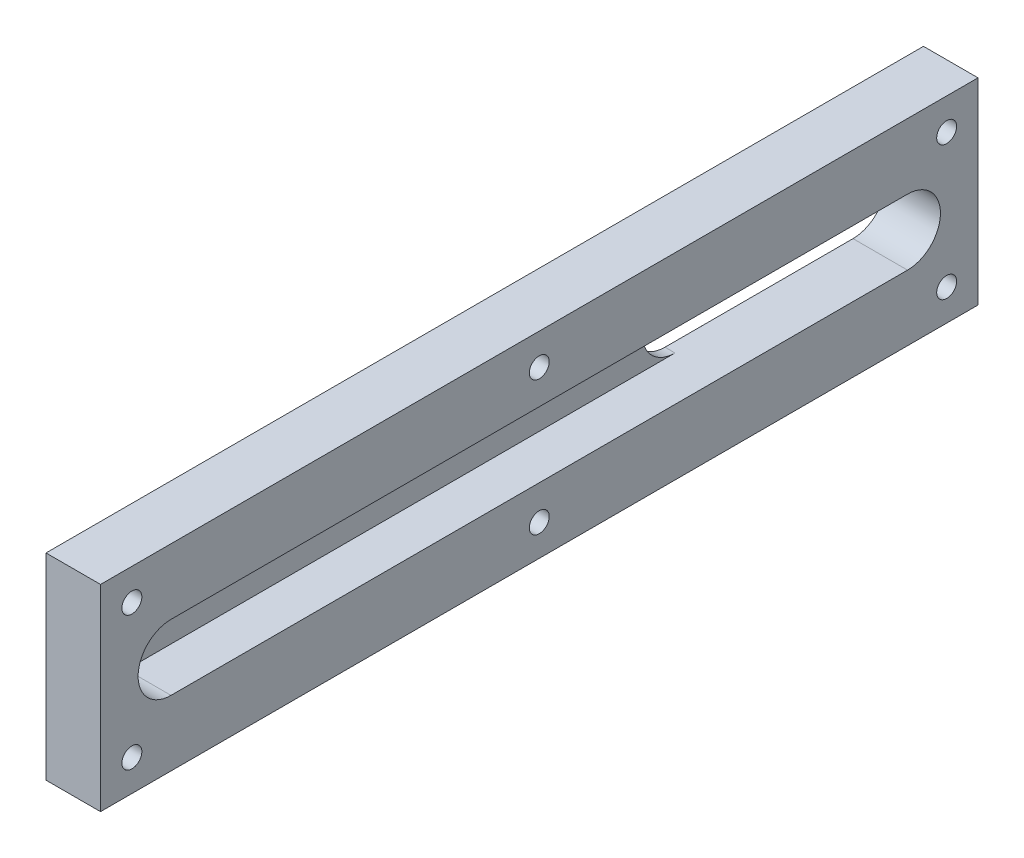
SolidWorks part; units mm, degrees
material "Delrin 2700 NC010, Low Viscosity Acetal Copolymer (SS)"
ref_plane "Front" through (0, 0, 0) normal (0, 0, 1) x (1, 0, 0)
ref_plane "Top" through (0, 0, 0) normal (0, 1, 0) x (1, 0, 0)
ref_plane "Right" through (0, 0, 0) normal (1, 0, 0) x (0, 0, -1)
sketch "Sketch1" plane through (0, 0, 0) normal (1, 0, 0) x (0, 0, -1)
  line L0 (-74.6213, 0) -> (74.6213, 0) construction
  line L1 (88.9, -19.939) -> (-88.9, -19.939)
  line L2 (88.9, -19.939) -> (88.9, 19.939)
  line L3 (88.9, 19.939) -> (-88.9, 19.939)
  line L4 (-88.9, -19.939) -> (-88.9, 19.939)
  line L5 (88.9, -19.939) -> (-88.9, 19.939) construction
  line L6 (88.9, 19.939) -> (-88.9, -19.939) construction
  line L7 (-74.6213, 6.6675) -> (74.6213, 6.6675)
  line L8 (-74.6213, -6.6675) -> (74.6213, -6.6675)
  arc A0 (-74.6213, 6.6675) -> (-74.6213, -6.6675) centre (-74.6213, 0) ccw
  arc A1 (74.6213, -6.6675) -> (74.6213, 6.6675) centre (74.6213, 0) ccw
  point P0 (0, 0)
  point P8 (0, 0)
  dimension "D4" = 13.335
  dimension "D1" = 149.2426
  dimension "D2" = 177.8
  dimension "D3" = 39.878
extrude "Boss-Extrude1" add sketch "Sketch1" along normal blind 11.049
hole_wizard "#10-32 Tapped Hole1" positions "Sketch3" profile "Sketch4" tap size "#10-32" standard "ANSI Inch" end condition through all
sketch "Sketch3" plane through (11.049, 0, 0) normal (1, 0, 0) x (0, 0, -1)
  line L0 (-82.55, 13.589) -> (0, 13.589) construction
  line L1 (0, 13.589) -> (82.55, 13.589) construction
  line L3 (-82.55, 19.939) -> (-82.55, 13.589) construction
  line L4 (88.9, 19.939) -> (-88.9, 19.939) construction
  line L5 (-82.55, 13.589) -> (-82.55, -13.589) construction
  line L6 (-82.55, -13.589) -> (-82.55, -19.939) construction
  line L7 (-88.9, -19.939) -> (88.9, -19.939) construction
  line L8 (-88.9, 19.939) -> (-88.9, -19.939) construction
  point P0 (-82.55, 13.589)
  point P2 (-82.55, -13.589)
  point P4 (0, -13.589)
  point P6 (82.55, -13.589)
  point P8 (82.55, 13.589)
  point P10 (0, 13.589)
  dimension "D1" = 6.35
  dimension "D2" = 6.35
sketch "Sketch4" plane through (11.049, 13.589, 82.55) normal (0, 1, 0) x (0, 0, -1)
  line L0 (0, 0) -> (0, 11.049)
  line L1 (0, 11.049) -> (2.0193, 11.049)
  line L2 (2.0193, 11.049) -> (2.0193, 0)
  line L5 (2.0193, 0) -> (0, 0)
  line L11 (0, -6.35) -> (0, 107.95) construction
  dimension "Thru Tap Drill Dia." = 4.0386
  dimension "Thru Tap Drill Depth" = 11.049
cosmetic thread "Hole Thread1" parameters "D2"=4.826
cosmetic thread "Hole Thread2" parameters "D2"=4.826
cosmetic thread "Hole Thread3" parameters "D2"=4.826
cosmetic thread "Hole Thread4" parameters "D2"=4.826
cosmetic thread "Hole Thread5" parameters "D2"=4.826
cosmetic thread "Hole Thread6" parameters "D2"=4.826
sketch "Sketch5" plane through (0, 0, 0) normal (-1, 0, 0) x (0, 0, 1)
  line L6 (-74.6213, -6.6675) -> (74.6213, -6.6675)
  line L7 (74.6213, 6.6675) -> (-74.6213, 6.6675)
  line L8 (-36.5213, -6.6675) -> (74.6213, -6.6675)
  line L9 (74.6213, 6.6675) -> (-36.5213, 6.6675)
  arc A2 (-36.5213, 6.6675) -> (-36.5213, -6.6675) centre (-36.5213, 0) cw
  arc A6 (-74.6213, 6.6675) -> (-74.6213, -6.6675) centre (-74.6213, 0) ccw construction
  arc A7 (74.6213, -6.6675) -> (74.6213, 6.6675) centre (74.6213, 0) ccw
  arc A8 (-74.6213, 6.6675) -> (-74.6213, -6.6675) centre (-74.6213, 0) ccw
  arc A9 (74.6213, -6.6675) -> (74.6213, 6.6675) centre (74.6213, 0) ccw
  dimension "D2" = 38.1
  dimension "D1" = 0
extrude "Boss-Extrude2" add sketch "Sketch5" against normal blind 2.032
